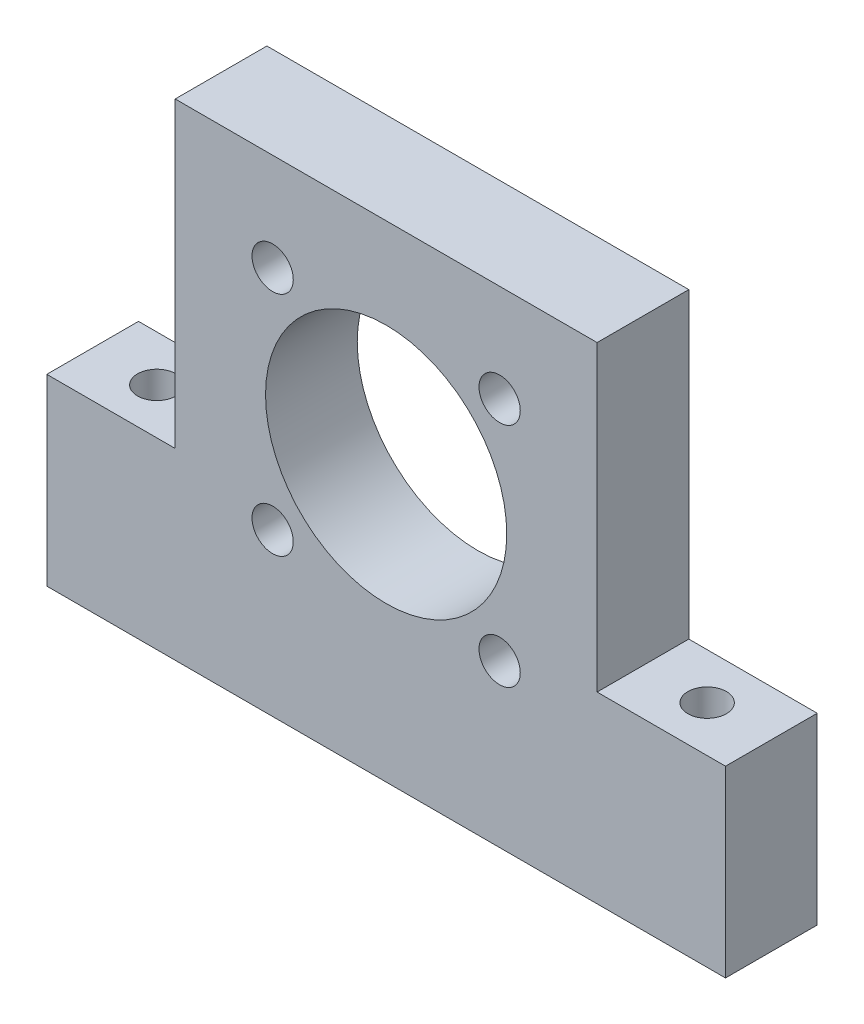
SolidWorks part; units mm, degrees
ref_plane "Plan de face" through (0, 0, 0) normal (0, 0, 1) x (1, 0, 0)
ref_plane "Plan de dessus" through (0, 0, 0) normal (0, 1, 0) x (1, 0, 0)
ref_plane "Plan de droite" through (0, 0, 0) normal (1, 0, 0) x (0, 0, -1)
sketch "Esquisse1" plane through (0, 0, 0) normal (0, 0, 1) x (1, 0, 0)
  line L0 (-23, 23) -> (23, 23)
  line L1 (-23, 23) -> (-23, -10)
  line L2 (23, 23) -> (23, -10)
  line L3 (23, -10) -> (37, -10)
  line L4 (-23, -10) -> (-37, -10)
  line L5 (-37, -10) -> (-37, -30)
  line L6 (37, -10) -> (37, -30)
  line L7 (-37, -30) -> (37, -30)
  circle A0 centre (0, 0) radius 13.15
  point P11 (0, 0)
  point P13 (34.9448, -9.7962)
  point P22 (22.5537, -22.1538)
  dimension "D7" = 26.3
  dimension "D1" = 46
  dimension "D2" = 74
  dimension "D4" = 14
  dimension "D5" = 33
  dimension "D6" = 20
  dimension "D9" = 23
  dimension "D10" = 30
extrude "Boss.-Extru.1" add sketch "Esquisse1" along normal blind 10
sketch "Esquisse5" plane through (0, -30, 0) normal (0, -1, 0) x (1, 0, 0)
  line L0 (-37, 10) -> (0, 10) construction
  line L1 (-37, 10) -> (37, 10) construction
  line L3 (0, 10) -> (0, 0) construction
  line L4 (-37, 0) -> (37, 0) construction
  line L5 (-37, 10) -> (-37, 0) construction
  circle A0 centre (-30, 5) radius 2.1
  circle A1 centre (30, 5) radius 2.1
  dimension "D1" = 7
  dimension "D2" = 4.2
  dimension "D3" = 5
extrude "Enlèv. mat.-Extru.2" cut sketch "Esquisse5" against normal up to next
sketch "Sketch1" plane through (0, 0, 10) normal (0, 0, 1) x (1, 0, 0)
  line L0 (12.3744, 12.3744) -> (0, 0) construction
  line L1 (0, 0) -> (0, 23) construction
  line L2 (23, 23) -> (-23, 23) construction
  circle A0 centre (12.3744, 12.3744) radius 2.25
  dimension "D1" = 4.5
  dimension "D2" = 45
  dimension "D3" = 17.5
extrude "Cut-Extrude1" cut sketch "Sketch1" against normal through all
pattern_circular "CirPattern1" count 4 over 360 about axis through (0, 0, 0) along (0, 0, 1) of "Cut-Extrude1"
